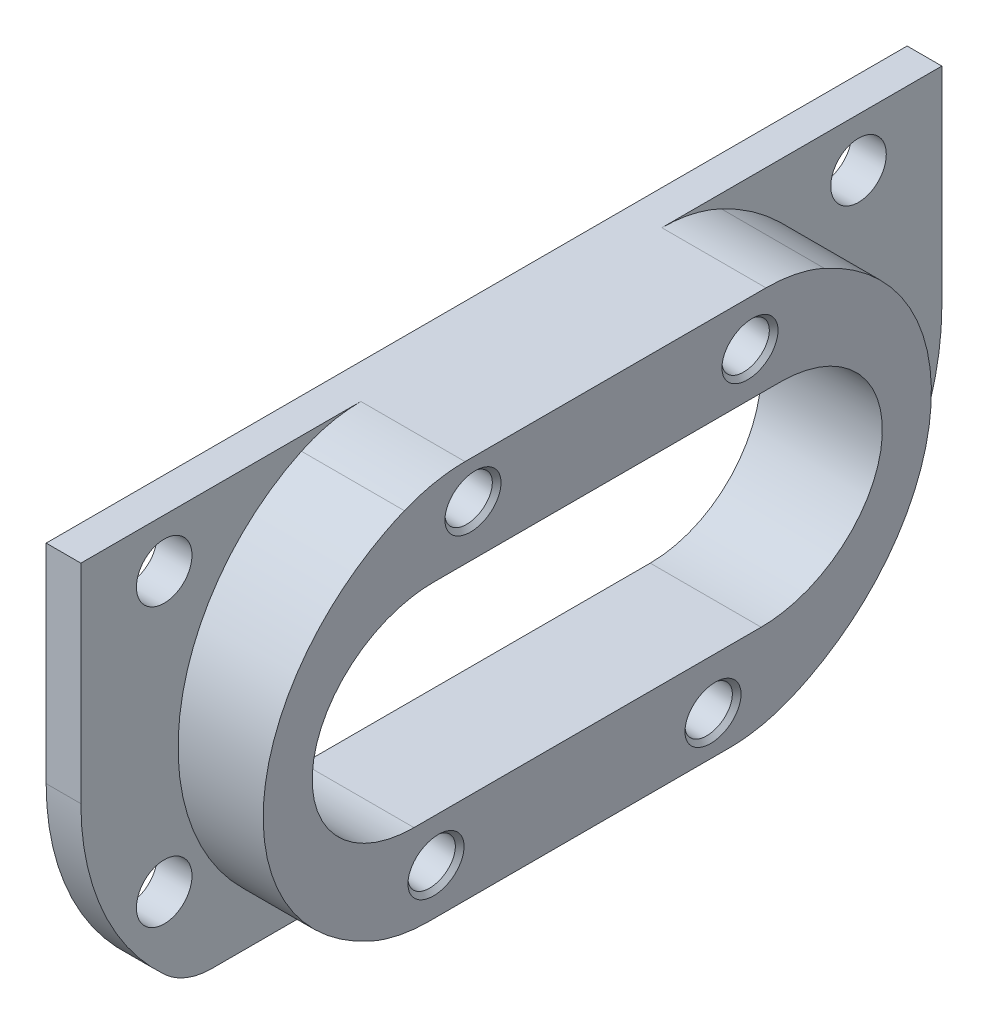
SolidWorks part; units mm, degrees
ref_plane "Płaszczyzna przednia" through (0, 0, 0) normal (0, 0, 1) x (1, 0, 0)
ref_plane "Płaszczyzna górna" through (0, 0, 0) normal (0, 1, 0) x (1, 0, 0)
ref_plane "Płaszczyzna prawa" through (0, 0, 0) normal (1, 0, 0) x (0, 0, -1)
sketch "Szkic1" plane through (0, 0, 0) normal (1, 0, 0) x (0, 0, -1)
  line L0 (-25, -16) -> (25, -16)
  line L1 (25, 16) -> (-25, 16)
  line L2 (-43.1384, -30) -> (43.1384, -30)
  line L3 (-62, 0) -> (62, 0) construction
  line L4 (-62, 30) -> (62, 30)
  line L5 (62, 0) -> (62, 30)
  line L6 (-62, 30) -> (-62, 0)
  line L7 (0, 0) -> (0, 30) construction
  arc A0 (-25, 16) -> (-25, -16) centre (-25, 0) ccw
  arc A1 (25, -16) -> (25, 16) centre (25, 0) ccw
  arc A2 (43.1384, -30) -> (49.8563, -27.4074) centre (43.1384, -20) ccw
  arc A3 (-49.8563, -27.4074) -> (-43.1384, -30) centre (-43.1384, -20) ccw
  arc A6 (49.8563, -27.4074) -> (62, 0) centre (25, 0) ccw
  arc A7 (-62, 0) -> (-49.8563, -27.4074) centre (-25, 0) ccw
  circle A8 centre (-50, 23) radius 4
  circle A9 centre (50, 23) radius 4
  circle A10 centre (50, -17) radius 4
  circle A11 centre (-50, -17) radius 4
  dimension "D2" = 16
  dimension "D3" = 10
  dimension "D4" = 7
  dimension "D5" = 37
  dimension "D10" = 8
  dimension "D1" = 50
  dimension "D6" = 43.1384
  dimension "D7" = 50
  dimension "D8" = 2
  dimension "D9" = 2
extrude "Dodanie-wyciągnięcie1" add sketch "Szkic1" along normal blind 20
sketch "Szkic2" plane through (20, 0, 0) normal (1, 0, 0) x (0, 0, -1)
  line L0 (-25, -16) -> (25, -16) construction
  line L1 (25, 16) -> (-25, 16) construction
  line L2 (-25, -16) -> (25, -16)
  line L3 (25, 16) -> (-25, 16)
  line L6 (21.6718, 30) -> (-21.6718, 30)
  line L7 (-21.6718, -30) -> (21.6718, -30)
  line L8 (0, 0) -> (0, 16) construction
  arc A0 (25, -16) -> (25, 16) centre (25, 0) ccw construction
  arc A1 (-25, 16) -> (-25, -16) centre (-25, 0) ccw construction
  arc A2 (25, -16) -> (25, 16) centre (25, 0) ccw
  arc A3 (-25, 16) -> (-25, -16) centre (-25, 0) ccw
  arc A6 (-30.2337, -28.0747) -> (-30.2337, 28.0747) centre (-16.9348, 0) cw
  arc A7 (30.2337, -28.0747) -> (30.2337, 28.0747) centre (16.9348, 0) ccw
  arc A8 (-30.2337, -28.0747) -> (-21.6718, -30) centre (-21.6718, -10) ccw
  arc A9 (21.6718, -30) -> (30.2337, -28.0747) centre (21.6718, -10) ccw
  arc A10 (30.2337, 28.0747) -> (21.6718, 30) centre (21.6718, 10) ccw
  arc A11 (-21.6718, 30) -> (-30.2337, 28.0747) centre (-21.6718, 10) ccw
  point P4 (-25, 0)
  point P5 (-25, 23)
  point P8 (-25, -23)
  point P9 (25, -23)
  point P10 (25, 0)
  point P11 (25, 23)
  point P23 (-25, -30)
  point P26 (25, -30)
  point P29 (25, 30)
  point P32 (-25, 30)
  dimension "D1" = 20
  dimension "D2" = 20
  dimension "D3" = 20
  dimension "D4" = 20
extrude "Wytnij-wyciągnięcie1" cut sketch "Szkic2" against normal blind 15 flip side to cut
sketch "Szkic3" plane through (0, 0, -62) normal (0, 0, -1) x (-1, 0, 0)
  line L4 (-5, 0) -> (-20, 0) construction
  line L5 (-20, 30) -> (-14.7507, -30)
  line L6 (-20, 30) -> (-20, -30)
  line L7 (-14.7507, -30) -> (-20, -30)
extrude "Wytnij-wyciągnięcie2" cut sketch "Szkic3" against normal through all both and the other way through all
sketch "Szkic9" plane through (17.2434, -1.5086, 0) normal (0.9962, -0.0872, 0) x (0, 0, -1)
  line L0 (0, 1.5144) -> (-41.9451, 2.6127) construction
  line L1 (0, 0) -> (0, 22.9605) construction
  line L2 (25, 17.5755) -> (-25, 17.5755)
  line L3 (-25, -14.5468) -> (25, -14.5468)
  line L4 (25, 17.5755) -> (-25, 17.5755)
  line L5 (-25, -14.5468) -> (25, -14.5468)
  line L7 (0, 0) -> (0, -18.3021) construction
  ellipse E2 centre (-25, 1.5144) end of major axis (-25, -14.5468) minor radius 16 (-25, 17.5755) -> (-25, -14.5468) ccw
  ellipse E3 centre (25, 1.5144) end of major axis (25, -14.5468) minor radius 16 (25, -14.5468) -> (25, 17.5755) ccw
  ellipse E4 centre (-25, 1.5144) end of major axis (-25, -14.5468) minor radius 16 (-25, 17.5755) -> (-25, -14.5468) ccw
  ellipse E5 centre (25, 1.5144) end of major axis (25, -14.5468) minor radius 16 (25, -14.5468) -> (25, 17.5755) ccw
  point P4 (-20, 25.5461)
  point P5 (0, 0)
  point P8 (19.9863, 24.4991)
  point P10 (18.756, -22.4848)
  point P12 (-21.2303, -21.4378)
  dimension "D2" = 23.5
  dimension "D3" = 20
  dimension "D6" = 88.5
  dimension "D1" = 0
  dimension "D4" = 2
  dimension "D5" = 2
hole_wizard "Otwór gwintowany M81" positions "Szkic 3D1" profile "Szkic11" tap size "M8" standard "ISO"
sketch3d "Szkic 3D1"
  point P25 (19.4698, 23.9403, 20)
  point P28 (19.3786, 22.8972, -19.9863)
  point P31 (15.3749, -22.8648, 21.2303)
  point P34 (15.2837, -23.9079, -18.756)
sketch "Szkic11" plane through (19.4698, 23.9403, 20) normal (0, 0, 1) x (0.0872, 0.9962, 0)
  line L0 (0, 0) -> (0, 15)
  line L1 (0, 15) -> (3.4, 12.9571)
  line L2 (3.4, 12.9571) -> (3.4, 0.625)
  line L3 (3.4, 0.625) -> (4.025, 0)
  line L5 (4.025, 0) -> (0, 0)
  line L6 (-3.4, 0.625) -> (-4.025, 0) construction
  line L10 (0, 15) -> (-3.4, 12.9571) construction
  line L11 (0, -6.35) -> (0, 107.95) construction
  dimension "Średnica wiertła gwintu" = 6.8
  dimension "Głębokość otworu gwintowanego" = 15
  dimension "Średnica zewnętrznego pogłębienia stożkowego" = 8.05
  dimension "Kąt zewnętrznego pogłębienia stożkowego" = 90
  dimension "Kąt wiertła" = 118
cosmetic thread "Gwint otworu1" parameters "D1"=12, "D2"=8
cosmetic thread "Gwint otworu2" parameters "D1"=12, "D2"=8
cosmetic thread "Gwint otworu3" parameters "D1"=12, "D2"=8
cosmetic thread "Gwint otworu4" parameters "D1"=12, "D2"=8
